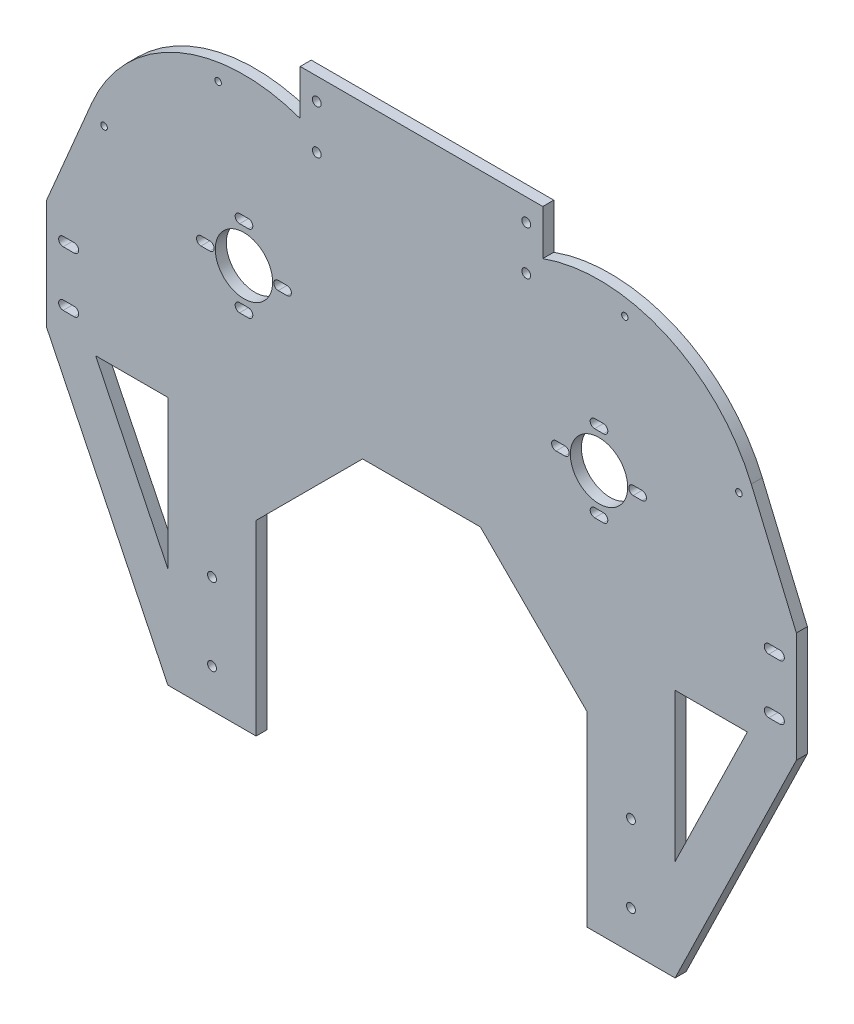
SolidWorks part; units mm, degrees
ref_plane "Front Plane" through (0, 0, 0) normal (0, 0, 1) x (1, 0, 0)
ref_plane "Top Plane" through (0, 0, 0) normal (0, 1, 0) x (1, 0, 0)
ref_plane "Right Plane" through (0, 0, 0) normal (1, 0, 0) x (0, 0, -1)
sketch "Sketch1" plane through (0, 0, 0) normal (0, 0, 1) x (1, 0, 0)
  line L1 (-100, -75) -> (100, -75)
  line L2 (-100, -75) -> (-100, 75)
  line L3 (-100, 75) -> (100, 75)
  line L4 (100, -75) -> (100, 75)
  line L5 (-100, -75) -> (100, 75) construction
  line L6 (-100, 75) -> (100, -75) construction
  line L8 (-47.5, 40) -> (47.5, 40) construction
  line L9 (0, 75) -> (0, -75) construction
  line L10 (-27, -44) -> (27, -44) construction
  line L11 (-27, -44) -> (-27, 28) construction
  line L12 (-27, 28) -> (27, 28) construction
  line L13 (27, -44) -> (27, 28) construction
  line L14 (-27, -44) -> (27, 28) construction
  line L15 (-27, 28) -> (27, -44) construction
  line L23 (-55, 70) -> (55, 70)
  line L24 (-55, 70) -> (-55, -70)
  line L25 (-55, -70) -> (55, -70)
  line L26 (55, 70) -> (55, -70)
  line L27 (-55, 70) -> (55, -70) construction
  line L28 (-55, -70) -> (55, 70) construction
  line L29 (-32.5, 70) -> (32.5, 70) construction
  line L30 (-32.5, 70) -> (-32.5, 55) construction
  line L31 (-32.5, 55) -> (32.5, 55) construction
  line L32 (32.5, 70) -> (32.5, 55) construction
  line L33 (-32.5, 70) -> (32.5, 55) construction
  line L34 (-32.5, 55) -> (32.5, 70) construction
  circle A2 centre (-47.5, 40) radius 2
  circle A3 centre (47.5, 40) radius 2
  circle A4 centre (-27, 28) radius 2 construction
  circle A5 centre (27, 28) radius 2 construction
  circle A6 centre (27, -44) radius 2 construction
  circle A7 centre (-27, -44) radius 2 construction
  circle A8 centre (-47.5, 60) radius 2
  circle A10 centre (47.5, 60) radius 2
  point P0 (0, 0)
  point P15 (0, 40)
  point P18 (0, -8)
  point P56 (0, 0)
  point P63 (0, 62.5)
  dimension "D3" = 4
  dimension "D4" = 20
  dimension "D5" = 4
  dimension "D8" = 4
  dimension "D1" = 150
  dimension "D2" = 200
  dimension "D6" = 72
  dimension "D7" = 54
  dimension "D14" = 30
  dimension "D15" = 140
  dimension "D16" = 110
  dimension "D17" = 95
  dimension "D18" = 12
  dimension "D19" = 15
  dimension "D20" = 65
extrude "Boss-Extrude1" add sketch "Sketch1" along normal blind 5 contours L23 L32 L31 L30 L24 L25 L26 A7 A6 A5 A4 A3 A2 | L2 L1 L4 L3
sketch "Sketch2" plane through (0, 0, 0) normal (0, 0, 1) x (1, 0, 0)
  line L0 (-55, -70) -> (-100.8579, -115.8579) construction
  line L1 (-55, 70) -> (-55, -70) construction
  line L2 (-55, -41.7157) -> (-115, -101.7157)
  line L3 (-26.7157, -70) -> (-86.7157, -130)
  line L4 (-55, -70) -> (55, -70) construction
  line L5 (-115, -101.7157) -> (-86.7157, -130)
  line L6 (-115, -101.7157) -> (-115, -203)
  line L7 (-75, -118.2843) -> (-75, -203)
  line L8 (-75, -203) -> (-115, -203)
  line L9 (0, 75) -> (0, -75) construction
  line L10 (-55, -41.7157) -> (-26.7157, -70)
  line L11 (-55, 70) -> (-55, -70) construction
  line L12 (-115, -203) -> (-75, -203) construction
  circle A0 centre (-95, -150.5) radius 2
  circle A1 centre (-95, -185.5) radius 2
  circle A2 centre (-95, -150.5) radius 2 construction
  circle A4 centre (-95, -185.5) radius 2 construction
  dimension "D1" = 135
  dimension "D2" = 40
  dimension "D3" = 40
  dimension "D4" = 75
  dimension "D5" = 0
extrude "Boss-Extrude2" add sketch "Sketch2" along normal blind 5
mirror "Mirror1" about plane through (0, 0, 0) normal (1, 0, 0) of "Boss-Extrude2"
sketch "Sketch3" plane through (0, 0, 5) normal (0, 0, 1) x (1, 0, 0)
  line L0 (0, 31.3301) -> (0, 52.1198) construction
  line L1 (-80.5, -21) -> (-92.2213, 45.4745) construction
  line L2 (-80.5, -21) -> (80.5, -21) construction
  line L3 (-80.5, -21) -> (-148, -21) construction
  line L4 (-80.5, -21) -> (-143.9293, 2.0864) construction
  line L5 (-82.5, -3.5) -> (-78.5, -3.5) construction
  line L6 (-82.5, -1.5) -> (-78.5, -1.5)
  line L7 (-82.5, -5.5) -> (-78.5, -5.5)
  line L8 (-82.5, -38.5) -> (-78.5, -38.5) construction
  line L9 (-82.5, -40.5) -> (-78.5, -40.5)
  line L10 (-82.5, -36.5) -> (-78.5, -36.5)
  line L11 (-96, -21) -> (-100, -21) construction
  line L12 (-96, -23) -> (-100, -23)
  line L13 (-96, -19) -> (-100, -19)
  line L14 (-80.5, -21) -> (-80.5, -13.7655) construction
  line L15 (-65, -21) -> (-61, -21) construction
  line L16 (-65, -23) -> (-61, -23)
  line L17 (-65, -19) -> (-61, -19)
  line L18 (82.5, -3.5) -> (78.5, -3.5) construction
  line L19 (82.5, -1.5) -> (78.5, -1.5)
  line L20 (82.5, -5.5) -> (78.5, -5.5)
  line L21 (65, -21) -> (61, -21) construction
  line L22 (65, -23) -> (61, -23)
  line L23 (65, -19) -> (61, -19)
  line L24 (96, -21) -> (100, -21) construction
  line L25 (96, -23) -> (100, -23)
  line L26 (96, -19) -> (100, -19)
  line L27 (82.5, -38.5) -> (78.5, -38.5) construction
  line L28 (82.5, -40.5) -> (78.5, -40.5)
  line L29 (82.5, -36.5) -> (78.5, -36.5)
  circle A0 centre (-80.5, -21) radius 75
  circle A1 centre (-80.5, -3.5) radius 2 construction
  circle A2 centre (80.5, -21) radius 75
  circle A3 centre (-80.5, -21) radius 60
  circle A4 centre (80.5, -21) radius 60
  circle A5 centre (-47.5, 40) radius 2 construction
  circle A6 centre (-47.5, 40) radius 2
  circle A7 centre (47.5, 40) radius 2
  circle A8 centre (-63, -21) radius 2 construction
  circle A9 centre (-80.5, -38.5) radius 2 construction
  circle A10 centre (-98, -21) radius 2 construction
  circle A11 centre (98, -21) radius 2 construction
  circle A12 centre (80.5, -38.5) radius 2 construction
  circle A13 centre (63, -21) radius 2 construction
  circle A14 centre (80.5, -3.5) radius 2 construction
  circle A15 centre (-80.5, -21) radius 13
  circle A16 centre (80.5, -21) radius 13
  circle A17 centre (-92.2213, 45.4745) radius 1.4732
  circle A18 centre (-143.9293, 2.0864) radius 1.4732
  circle A19 centre (-80.5, -21) radius 67.5 construction
  circle A20 centre (92.2213, 45.4745) radius 1.4732
  circle A21 centre (143.9293, 2.0864) radius 1.4732
  arc A22 (-82.5, -1.5) -> (-82.5, -5.5) centre (-82.5, -3.5) ccw
  arc A23 (-78.5, -5.5) -> (-78.5, -1.5) centre (-78.5, -3.5) ccw
  arc A24 (-82.5, -40.5) -> (-82.5, -36.5) centre (-82.5, -38.5) cw
  arc A25 (-78.5, -36.5) -> (-78.5, -40.5) centre (-78.5, -38.5) cw
  arc A26 (-96, -23) -> (-96, -19) centre (-96, -21) ccw
  arc A27 (-100, -19) -> (-100, -23) centre (-100, -21) ccw
  arc A28 (-65, -23) -> (-65, -19) centre (-65, -21) cw
  arc A29 (-61, -19) -> (-61, -23) centre (-61, -21) cw
  arc A30 (82.5, -1.5) -> (82.5, -5.5) centre (82.5, -3.5) cw
  arc A31 (78.5, -5.5) -> (78.5, -1.5) centre (78.5, -3.5) cw
  arc A32 (65, -23) -> (65, -19) centre (65, -21) ccw
  arc A33 (61, -19) -> (61, -23) centre (61, -21) ccw
  arc A34 (96, -23) -> (96, -19) centre (96, -21) cw
  arc A35 (100, -19) -> (100, -23) centre (100, -21) cw
  arc A36 (82.5, -40.5) -> (82.5, -36.5) centre (82.5, -38.5) ccw
  arc A37 (78.5, -36.5) -> (78.5, -40.5) centre (78.5, -38.5) ccw
  point P28 (-80.5, -21)
  point P48 (-80.5, -3.5)
  point P53 (-98, -21)
  point P60 (-63, -21)
  point P67 (-80.5, -38.5)
  point P77 (80.5, -3.5)
  point P84 (63, -21)
  point P91 (98, -21)
  point P98 (80.5, -38.5)
  line M3 (115, -101.7157) -> (55, -41.7157)
  line M4 (55, -41.7157) -> (55, 70)
  line M6 (-55, 70) -> (-55, -41.7157)
  line M7 (-55, -41.7157) -> (-115, -101.7157)
  line M11 (-75, -118.2843) -> (-26.7157, -70)
  line M12 (-26.7157, -70) -> (26.7157, -70)
  line M13 (26.7157, -70) -> (75, -118.2843)
  circle M17 centre (-47.5, 40) radius 2
  circle M18 centre (47.5, 40) radius 2
  dimension "D1" = 161
  dimension "D2" = 150
  dimension "D3" = 61
  dimension "D4" = 120
  dimension "D5" = 4
  dimension "D7" = 2
  dimension "D8" = 26
  dimension "D9" = 7.5
  dimension "D10" = 2.9464
  dimension "D15" = 2
  dimension "D6" = 4
  dimension "D11" = 80
  dimension "D12" = 20
  dimension "D13" = 17.5
  dimension "D14" = 4
  dimension "D16" = 4
extrude "Boss-Extrude3" add sketch "Sketch3" against normal up to surface (5 mm away) contours A3 M6 M7 | A3 A0 M6 M7 | A3 A0 M7 M11 M12 M6 M17 | A3 M7 M6 | A4 M3 M4 | A4 M4 M3 | A4 A2 M4 M3 | A4 A2 M3 M4 M12 M13 M18
sketch "Sketch4" plane through (0, 0, 5) normal (0, 0, 1) x (1, 0, 0)
  line L0 (-170, -90) -> (-115, -203)
  line L1 (-100, -40) -> (-153.0534, -40)
  line L2 (-100, -40) -> (-100, -90)
  line L3 (-100, -90) -> (-115, -90) construction
  line L4 (-170, -40) -> (-170, -90)
  line L5 (-100, -40) -> (-170, -90) construction
  line L6 (-100, -90) -> (-170, -40) construction
  line L7 (-147.7568, -90) -> (-115, -157.3003)
  line L8 (-115, -101.7157) -> (-115, -203) construction
  line L9 (-170, -40) -> (-149.5595, 8.2539)
  line L10 (-100, -90) -> (-115, -90) construction
  line L11 (-100, -90) -> (-100, -101.7157)
  line L12 (-100, -101.7157) -> (-115, -101.7157)
  line L13 (-115, -90) -> (-115, -101.7157)
  line L14 (-100, -90) -> (-115, -101.7157) construction
  line L15 (-100, -101.7157) -> (-115, -90) construction
  line L16 (-153.0534, -40) -> (-170, -40) construction
  line L17 (-147.7568, -90) -> (-170, -90) construction
  line L18 (-115, -90) -> (-147.7568, -90)
  line L19 (-115, -157.3003) -> (-115, -203)
  line L20 (-170, -65) -> (-100, -65) construction
  line L21 (-160, -40) -> (-160, -65) construction
  line L22 (-157.5, -52.5) -> (-162.5, -52.5) construction
  line L23 (-157.5, -54.55) -> (-162.5, -54.55)
  line L24 (-157.5, -50.45) -> (-162.5, -50.45)
  line L25 (-157.5, -77.5) -> (-162.5, -77.5) construction
  line L26 (-157.5, -75.45) -> (-162.5, -75.45)
  line L27 (-157.5, -79.55) -> (-162.5, -79.55)
  arc A0 (-55, 49.5319) -> (-105.1261, -91.8418) centre (-80.5, -21) ccw construction
  arc A1 (-149.5595, 8.2539) -> (-153.0534, -40) centre (-80.5, -21) ccw
  circle A2 centre (-160, -52.5) radius 2.05 construction
  arc A3 (-157.5, -54.55) -> (-157.5, -50.45) centre (-157.5, -52.5) ccw
  arc A4 (-162.5, -50.45) -> (-162.5, -54.55) centre (-162.5, -52.5) ccw
  arc A5 (-157.5, -75.45) -> (-157.5, -79.55) centre (-157.5, -77.5) cw
  arc A6 (-162.5, -79.55) -> (-162.5, -75.45) centre (-162.5, -77.5) cw
  point P4 (-135, -65)
  point P15 (-107.5, -95.8579)
  point P29 (-160, -52.5)
  point P36 (0, 0)
  point P39 (-160, -77.5)
  dimension "D6" = 4.1
  dimension "D8" = 2.05
  dimension "D1" = 40
  dimension "D2" = 100
  dimension "D3" = 70
  dimension "D4" = 50
  dimension "D5" = 20
  dimension "D7" = 10
  dimension "D9" = 5
extrude "Boss-Extrude4" add sketch "Sketch4" against normal up to surface (5 mm away) up to face at (0, -80.3864, 0)
mirror "Mirror2" about plane through (0, 0, 0) normal (1, 0, 0) of "Boss-Extrude4"
